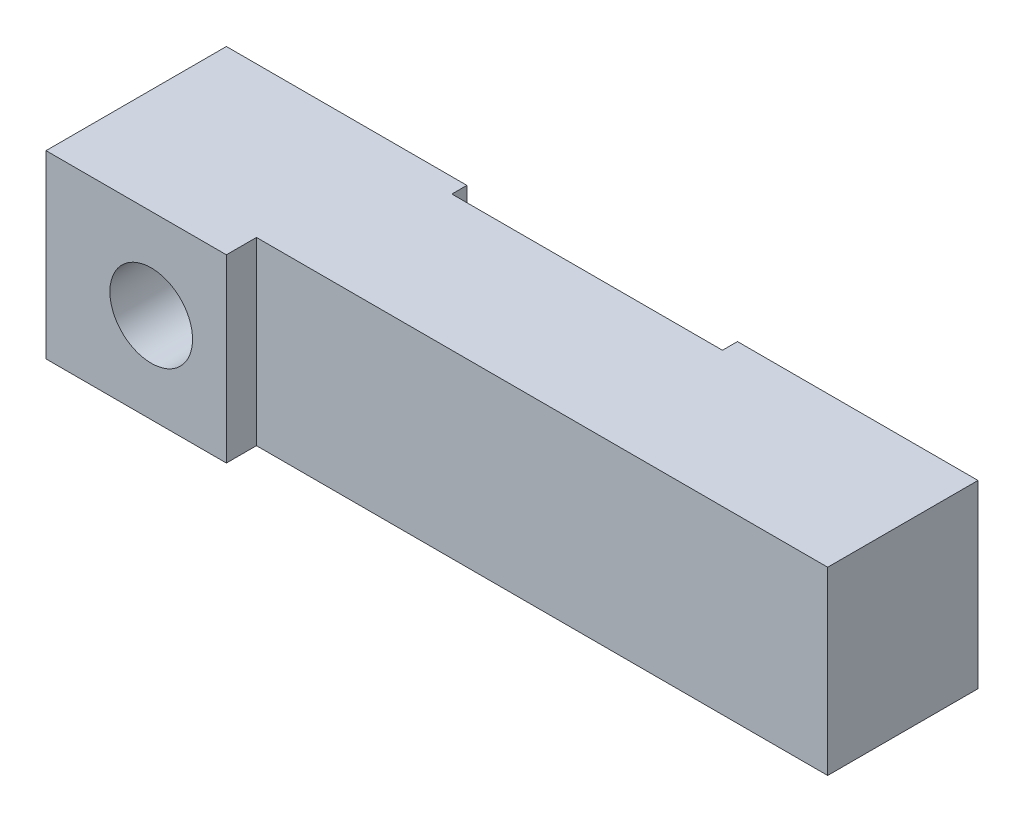
SolidWorks part; units mm, degrees
ref_plane "Plan de face" through (0, 0, 0) normal (0, 0, 1) x (1, 0, 0)
ref_plane "Plan de dessus" through (0, 0, 0) normal (0, 1, 0) x (1, 0, 0)
ref_plane "Plan de droite" through (0, 0, 0) normal (1, 0, 0) x (0, 0, -1)
sketch "Esquisse1" plane through (0, 0, 0) normal (0, 0, 1) x (1, 0, 0)
  line L1 (-25, 6) -> (25, 6)
  line L2 (-25, 6) -> (-25, -6)
  line L3 (-25, -6) -> (25, -6)
  line L4 (25, 6) -> (25, -6)
  line L5 (-25, 6) -> (25, -6) construction
  line L6 (-25, -6) -> (25, 6) construction
  point P0 (0, 0)
  dimension "D1" = 12
  dimension "D2" = 50
extrude "Boss.-Extru.1" add sketch "Esquisse1" along normal blind 10
sketch "Esquisse3" plane through (0, 0, 10) normal (0, 0, 1) x (1, 0, 0)
  line L0 (-25, -6) -> (25, -6) construction
  line L1 (-25, 6) -> (-13, 6)
  line L2 (-25, 6) -> (-25, -6)
  line L3 (-25, -6) -> (-13, -6)
  line L4 (-13, 6) -> (-13, -6)
  dimension "D1" = 12
extrude "Boss.-Extru.2" add sketch "Esquisse3" along normal blind 2
sketch "Esquisse2" plane through (0, 0, 0) normal (0, 0, 1) x (1, 0, 0)
  line L0 (-25, 0) -> (25, 0) construction
  line L1 (-25, 6) -> (-25, -6) construction
  line L2 (25, -6) -> (25, 6) construction
  line L3 (0, 0) -> (0, 4.7687) construction
  circle A0 centre (-20, 0) radius 2.25
  circle A1 centre (20, 0) radius 3
  point P11 (20, 0)
  dimension "D1" = 4.5
  dimension "D2" = 6
  dimension "D3" = 40
sketch "Esquisse4" plane through (0, 0, 0) normal (0, 1, 0) x (1, 0, 0)
  line L0 (0, 0) -> (0, -10) construction
  line L1 (-9, -1) -> (9, -1)
  line L2 (-9, -1) -> (-9, 2.4984)
  line L3 (-9, 2.4984) -> (9, 2.4984)
  line L4 (9, -1) -> (9, 2.4984)
  line L5 (25, 0) -> (-25, 0) construction
  line L6 (25, -10) -> (-13, -10) construction
  dimension "D1" = 18
  dimension "D2" = 1
extrude "Enlèv. mat.-Extru.3" cut sketch "Esquisse4" against normal through all and the other way through all
hole_wizard "Chambrage pour vis à tête hexagonale M52" positions "Esquisse5" profile "Esquisse6" counterbore size "M5" standard "ISO" end condition through all
sketch "Esquisse5" plane through (0, 0, 0) normal (0, 0, -1) x (-1, 0, 0)
  line L0 (25, 6) -> (25, -6) construction
  line L1 (25, 0) -> (-25, 0) construction
  point P0 (18, 0)
  point P5 (0, 0)
  dimension "D1" = 7
sketch "Esquisse6" plane through (-18, 0, 0) normal (1, 0, 0) x (0, 1, 0)
  line L0 (0, 0) -> (0, 12)
  line L1 (0, 12) -> (2.75, 12)
  line L3 (2.75, 12) -> (2.75, 5.4)
  line L4 (2.75, 5.4) -> (5, 5.4)
  line L5 (5, 5.4) -> (5, 0)
  line L7 (5, 0) -> (0, 0)
  line L11 (0, -6.35) -> (0, 107.95) construction
  dimension "Diamètre du perçage jusqu'au prochain" = 5.5
  dimension "Profondeur du perçage jusqu'au prochain" = 12
  dimension "Diamètre du chambrage" = 10
  dimension "Profondeur du chambrage" = 5.4
